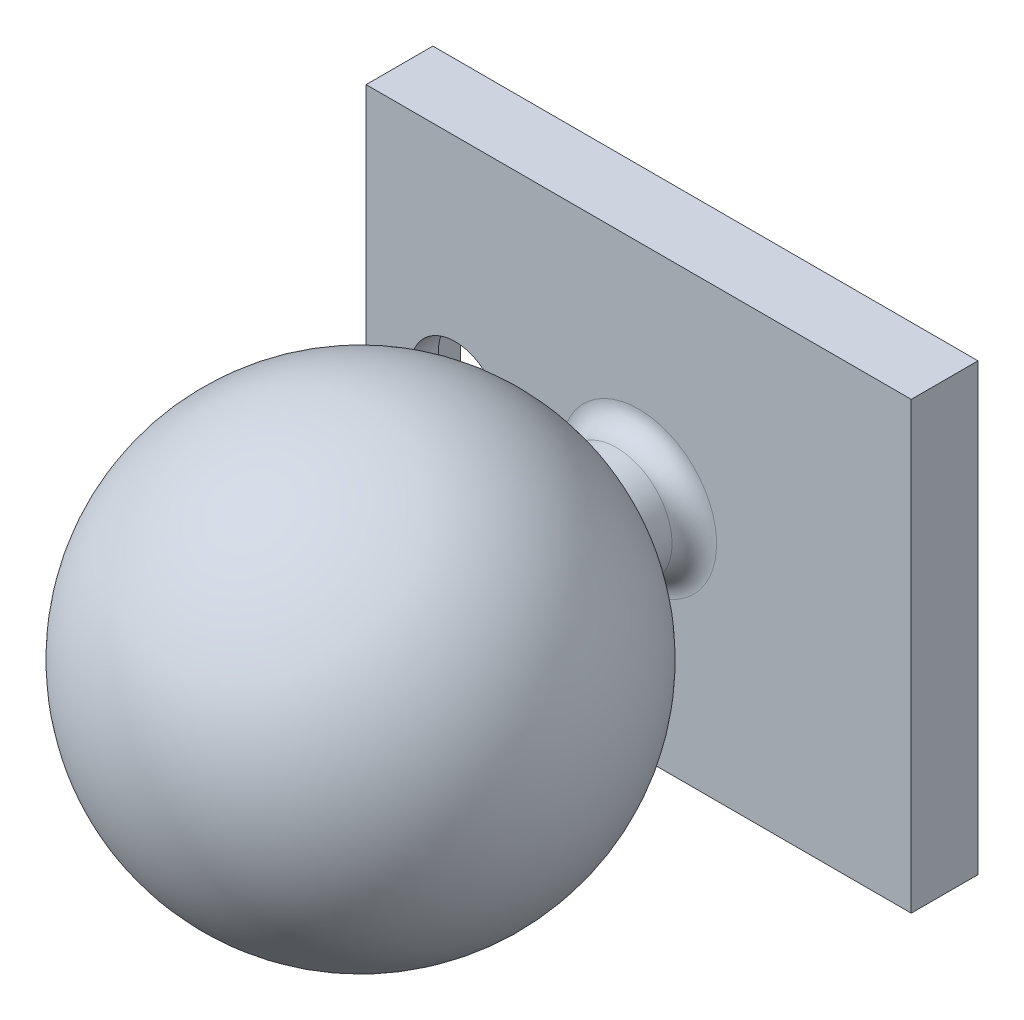
SolidWorks part; units mm, degrees
ref_plane "Front Plane" through (0, 0, 0) normal (0, 0, 1) x (1, 0, 0)
ref_plane "Top Plane" through (0, 0, 0) normal (0, 1, 0) x (1, 0, 0)
ref_plane "Right Plane" through (0, 0, 0) normal (1, 0, 0) x (0, 0, -1)
sketch "Sketch1" plane through (0, 0, 0) normal (0, 0, 1) x (1, 0, 0)
  line L1 (-27.94, -22.225) -> (27.94, -22.225)
  line L2 (-27.94, -22.225) -> (-27.94, 22.225)
  line L3 (-27.94, 22.225) -> (27.94, 22.225)
  line L4 (27.94, -22.225) -> (27.94, 22.225)
  line L5 (-27.94, -22.225) -> (27.94, 22.225) construction
  line L6 (-27.94, 22.225) -> (27.94, -22.225) construction
  point P0 (0, 0)
  dimension "D1" = 55.88
  dimension "D2" = 44.45
extrude "Boss-Extrude1" add sketch "Sketch1" along normal blind 3.175
sketch "Sketch2" plane through (0, 0, 3.175) normal (0, 0, 1) x (1, 0, 0)
  line L8 (31.115, -25.4) -> (31.115, 25.4)
  line L9 (31.115, 25.4) -> (-31.115, 25.4)
  line L10 (-31.115, 25.4) -> (-31.115, -25.4)
  line L11 (-31.115, -25.4) -> (31.115, -25.4)
  line L12 (31.115, -25.4) -> (31.115, 25.4)
  line L13 (31.115, 25.4) -> (-31.115, 25.4)
  line L14 (-31.115, 25.4) -> (-31.115, -25.4)
  line L15 (-31.115, -25.4) -> (31.115, -25.4)
  line L16 (27.94, -22.225) -> (27.94, 22.225)
  line L17 (27.94, 22.225) -> (-27.94, 22.225)
  line L18 (-27.94, 22.225) -> (-27.94, -22.225)
  line L19 (-27.94, -22.225) -> (27.94, -22.225)
  line L20 (27.94, -22.225) -> (27.94, 22.225)
  line L21 (27.94, 22.225) -> (-27.94, 22.225)
  line L22 (-27.94, 22.225) -> (-27.94, -22.225)
  line L23 (-27.94, -22.225) -> (27.94, -22.225)
  dimension "D1" = 3.175
  dimension "D2" = 0
extrude "Boss-Extrude2" add sketch "Sketch2" against normal blind 7.62
sketch "Sketch3" plane through (0, 0, 0) normal (0, 1, 0) x (1, 0, 0)
  line L0 (0, 0) -> (0, -25.7673) construction
  line L1 (31.115, -3.175) -> (-31.115, -3.175) construction
  line L2 (0, -3.175) -> (6.35, -3.175)
  line L5 (6.35, -3.175) -> (6.35, -10.3316)
  line L6 (0, -60.325) -> (0, -3.175)
  arc A0 (6.35, -10.3316) -> (0, -60.325) centre (0, -34.925) cw
  point P2 (0, 0)
  point P4 (-2.1061, -3.175)
  point P5 (0, -54.8932)
  point P10 (0, -66.2625)
  dimension "D2" = 25.4
  dimension "D1" = 6.35
  dimension "D3" = 31.75
revolve "Revolve1" add sketch "Sketch3" angle 360 about L0
fillet "Fillet1" radius 2.54 2 edges at (-6.35, 0, 10.3316) (-6.35, 0, 3.175)
sketch "Sketch4" plane through (0, 0, 3.175) normal (0, 0, 1) x (1, 0, 0)
  line L0 (-31.115, 25.4) -> (-31.115, -25.4) construction
  circle A0 centre (-20.955, 0) radius 5.08
  dimension "D2" = 10.16
  dimension "D1" = 10.16
extrude "Cut-Extrude1" cut sketch "Sketch4" against normal blind 15.875
sketch "Sketch5" plane through (0, 0, 0) normal (0, 0, -1) x (-1, 0, 0)
  point P0 (0, 0)
